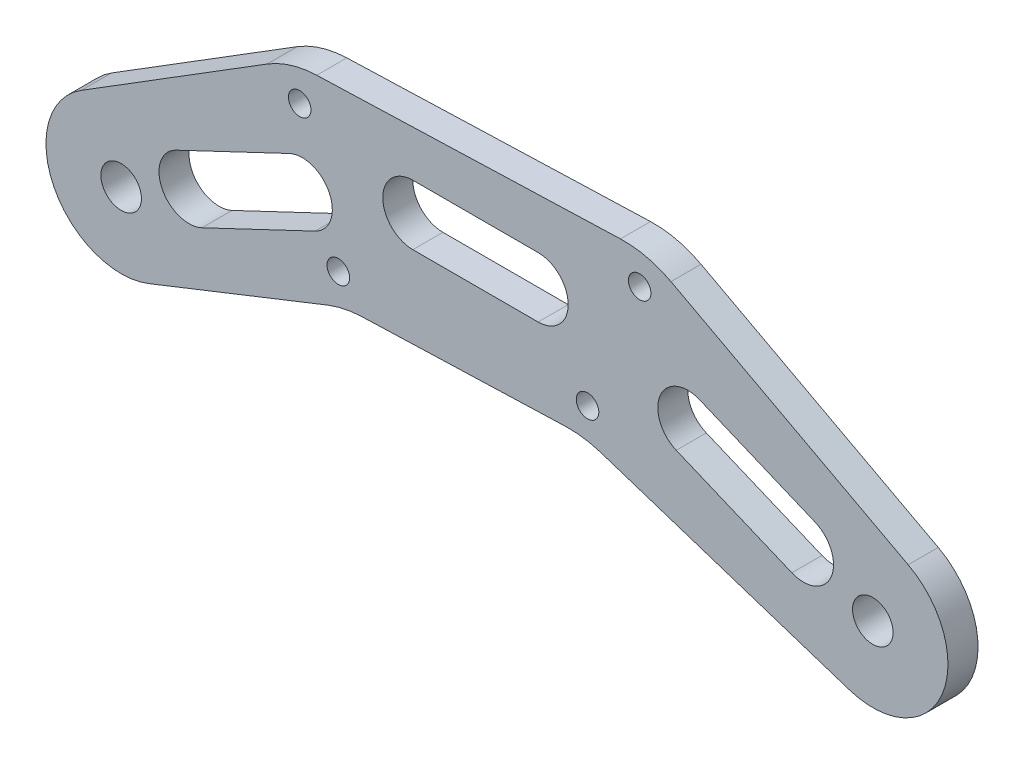
SolidWorks part; units mm, degrees
material "1060 Alloy"
ref_plane "Front Plane" through (0, 0, 0) normal (0, 0, 1) x (1, 0, 0)
ref_plane "Top Plane" through (0, 0, 0) normal (0, 1, 0) x (1, 0, 0)
ref_plane "Right Plane" through (0, 0, 0) normal (1, 0, 0) x (0, 0, -1)
sketch "Sketch1" plane through (0, 0, 0) normal (0, 0, 1) x (1, 0, 0)
  line L0 (-70.7116, -24.2666) -> (-32.512, -0.4802) construction
  line L1 (-32.512, -0.4802) -> (30.767, 1.6301) construction
  line L2 (30.767, 1.6301) -> (79.2884, -24.2671) construction
  line L3 (-65.1906, -38.2136) -> (-29.435, -24.0597)
  line L4 (-22.7403, -22.6668) -> (18.0348, -21.307)
  line L5 (-68.9461, -11.387) -> (-40.7958, 6.1419) construction
  line L6 (-78.6403, -11.5334) -> (-41.5781, 11.5449)
  line L7 (-31.6729, 14.5562) -> (28.928, 16.5771)
  line L8 (39.0118, 14.2324) -> (86.3513, -11.034)
  line L9 (74.6308, -38.5257) -> (24.9116, -22.2845)
  line L10 (-24.6554, -17.7279) -> (19.5563, -16.2535) construction
  line L11 (38.3913, 8.896) -> (76.6688, -11.5338) construction
  line L12 (68.2873, -31.1935) -> (44.8744, -23.5455) construction
  line L13 (-59.3074, -30.5072) -> (-37.2698, -21.7836) construction
  line L14 (-35.5233, 9.425) -> (-27.2422, -17.8142) construction
  line L15 (33.1117, 11.7138) -> (22.2738, -16.1629) construction
  line L16 (-1.2069, 10.6036) -> (-0.3226, -15.9159) construction
  line L17 (-29.3156, 9.632) -> (26.678, 11.4993) construction
  line L18 (-35.8839, 2.0162) -> (-31.4035, -12.7213) construction
  line L19 (-31.1001, 3.4706) -> (-24.6554, -17.7279) construction
  line L20 (32.905, 4.2829) -> (24.6539, -16.9403) construction
  line L21 (55.2105, -4.18) -> (49.1505, -15.5341) construction
  line L22 (33.6271, -19.8715) -> (24.6539, -16.9403) construction
  line L23 (28.2448, 6.0946) -> (19.5563, -16.2535) construction
  line L24 (-45.4998, -8.5675) -> (-42.0019, -14.185) construction
  line L26 (-85.7116, 18.7334) -> (94.2884, 18.7334) construction
  line L27 (-85.7116, 18.7334) -> (-85.7116, -39.2666) construction
  line L28 (-85.7116, -39.2666) -> (94.2884, -39.2666) construction
  line L29 (94.2884, 18.7334) -> (94.2884, -39.2666) construction
  arc A0 (-65.1906, -38.2136) -> (-78.6403, -11.5334) centre (-70.7116, -24.2666) cw
  arc A1 (74.6308, -38.5257) -> (86.3513, -11.034) centre (79.2884, -24.2671) ccw
  circle A2 centre (-70.7116, -24.2666) radius 4.05
  circle A3 centre (79.2884, -24.2671) radius 4.05
  arc A4 (-31.1001, 3.4706) -> (-29.3156, 9.632) centre (-35.0785, 7.9619) ccw construction
  arc A5 (-59.3074, -30.5072) -> (-68.9461, -11.387) centre (-70.7116, -24.2666) ccw construction
  arc A6 (76.6688, -11.5338) -> (68.2873, -31.1935) centre (79.2884, -24.2671) ccw construction
  arc A7 (26.678, 11.4993) -> (28.2448, 6.0946) centre (32.5513, 10.2724) ccw construction
  arc A8 (32.905, 4.2829) -> (38.3913, 8.896) centre (32.5513, 10.2724) ccw construction
  arc A9 (-40.7958, 6.1419) -> (-35.8839, 2.0162) centre (-35.0785, 7.9619) ccw construction
  arc A10 (24.9116, -22.2845) -> (18.0348, -21.307) centre (18.7014, -41.2959) ccw
  arc A11 (-29.435, -24.0597) -> (-22.7403, -22.6668) centre (-22.0738, -42.6557) cw
  arc A12 (28.928, 16.5771) -> (39.0118, 14.2324) centre (29.5946, -3.4118) cw
  arc A13 (-41.5781, 11.5449) -> (-31.6729, 14.5562) centre (-31.0063, -5.4327) cw
  arc A14 (44.8744, -23.5455) -> (33.6271, -19.8715) centre (39.5613, -20.7579) ccw construction
  arc A15 (-31.4035, -12.7213) -> (-37.2698, -21.7836) centre (-32.1371, -18.6763) ccw construction
  point P57 (-0.7648, -2.6561)
  dimension "D9" = 8.1
  dimension "D10" = 12
  dimension "D11" = 20
  dimension "D14" = 15
  dimension "D15" = 15
  dimension "D1" = 150
  dimension "D2" = 150
  dimension "D3" = 55
  dimension "D4" = 150
  dimension "D5" = 45
  dimension "D6" = 22.5
  dimension "D7" = 10
  dimension "D8" = 15
  dimension "D12" = 30.7
  dimension "D13" = 29.7
  dimension "D16" = 58
extrude "Boss-Extrude1" add sketch "Sketch1" along normal blind 6 contours L6 A13 L7 A12 L8 A1 L9 A10 L4 A11 L3 A0
sketch "Sketch2" plane through (0, 0, 6) normal (0, 0, 1) x (1, 0, 0)
  line L6 (-35.0785, 7.9619) -> (-27.3698, -17.2008) construction
  line L7 (32.7653, 10.2244) -> (22.3603, -15.5547) construction
  line L12 (-67.399, -32.6348) -> (-31.6434, -18.4809)
  line L13 (-22.9403, -16.6701) -> (17.8348, -15.3104)
  line L14 (26.7746, -16.5811) -> (76.4939, -32.8222)
  line L15 (83.5262, -16.3272) -> (36.1866, 8.9391)
  line L16 (29.128, 10.5804) -> (-31.4729, 8.5595)
  line L17 (-38.4065, 6.4516) -> (-75.4688, -16.6266)
  line L18 (-67.399, -32.6348) -> (-31.6434, -18.4809) construction
  line L19 (-22.9403, -16.6701) -> (17.8348, -15.3104) construction
  line L20 (26.7746, -16.5811) -> (76.4939, -32.8222) construction
  line L21 (83.5262, -16.3272) -> (36.1866, 8.9391) construction
  line L22 (29.128, 10.5804) -> (-31.4729, 8.5595) construction
  line L23 (-38.4065, 6.4516) -> (-75.4688, -16.6266) construction
  arc A12 (-75.4688, -16.6266) -> (-67.399, -32.6348) centre (-70.7116, -24.2666) ccw
  arc A13 (-22.9403, -16.6701) -> (-31.6434, -18.4809) centre (-22.0738, -42.6557) ccw
  arc A14 (26.7746, -16.5811) -> (17.8348, -15.3104) centre (18.7014, -41.2959) ccw
  arc A15 (76.4939, -32.8222) -> (83.5262, -16.3272) centre (79.2884, -24.2671) ccw
  arc A16 (36.1866, 8.9391) -> (29.128, 10.5804) centre (29.5946, -3.4118) ccw
  arc A17 (-31.4729, 8.5595) -> (-38.4065, 6.4516) centre (-31.0063, -5.4327) ccw
  arc A18 (-75.4688, -16.6266) -> (-67.399, -32.6348) centre (-70.7116, -24.2666) ccw construction
  arc A19 (-22.9403, -16.6701) -> (-31.6434, -18.4809) centre (-22.0738, -42.6557) ccw construction
  arc A20 (26.7746, -16.5811) -> (17.8348, -15.3104) centre (18.7014, -41.2959) ccw construction
  arc A21 (76.4939, -32.8222) -> (83.5262, -16.3272) centre (79.2884, -24.2671) ccw construction
  arc A22 (36.1866, 8.9391) -> (29.128, 10.5804) centre (29.5946, -3.4118) ccw construction
  arc A23 (-31.4729, 8.5595) -> (-38.4065, 6.4516) centre (-31.0063, -5.4327) ccw construction
  dimension "D1" = 6
hole_wizard "M4 Clearance Hole1" positions "3DSketch1" profile "Sketch3" hole size "M4" standard "DIN"
sketch3d "3DSketch1"
  point P0 (-35.0785, 7.9619, 6)
  point P3 (-27.3698, -17.2008, 6)
  point P6 (32.7653, 10.2244, 6)
  point P9 (22.3603, -15.5547, 6)
sketch "Sketch3" plane through (-35.0785, 7.9619, 6) normal (1, 0, 0) x (0, -1, 0)
  line L0 (0, 0) -> (0, 82.3119)
  line L1 (0, 82.3119) -> (2.25, 80.96)
  line L2 (2.25, 80.96) -> (2.25, 0)
  line L5 (2.25, 0) -> (0, 0)
  line L10 (0, 82.3119) -> (-2.25, 80.96) construction
  line L11 (0, -6.35) -> (0, 107.95) construction
  dimension "Hole Dia." = 4.5
  dimension "Hole Depth" = 80.96
  dimension "Drill Angle" = 118
sketch "Sketch4" plane through (0, 0, 6) normal (0, 0, 1) x (1, 0, 0)
  line L0 (-57.1589, -17.838) -> (-34.5712, -7.1237) construction
  line L1 (-59.7304, -12.4169) -> (-37.1427, -1.7027)
  line L2 (-54.5875, -23.259) -> (-31.9998, -12.5448)
  line L3 (-70.7116, -24.2666) -> (-31.0063, -5.4327) construction
  line L4 (65.447, -18.4866) -> (42.378, -8.8523) construction
  line L5 (63.1348, -24.0231) -> (40.0657, -14.3889)
  line L6 (67.7592, -12.95) -> (44.6902, -3.3157)
  line L7 (79.2884, -24.2671) -> (27.5628, -2.6651) construction
  line L8 (-12.5, 0) -> (12.5, 0) construction
  line L9 (-12.5, 6) -> (12.5, 6)
  line L10 (-12.5, -6) -> (12.5, -6)
  line L12 (32.7653, 10.2244) -> (22.3603, -15.5547) construction
  arc A0 (-59.7304, -12.4169) -> (-54.5875, -23.259) centre (-57.1589, -17.838) ccw
  arc A1 (-31.9998, -12.5448) -> (-37.1427, -1.7027) centre (-34.5712, -7.1237) ccw
  arc A2 (63.1348, -24.0231) -> (67.7592, -12.95) centre (65.447, -18.4866) ccw
  arc A3 (44.6902, -3.3157) -> (40.0657, -14.3889) centre (42.378, -8.8523) ccw
  circle A4 centre (79.2884, -24.2671) radius 4.05 construction
  arc A5 (-12.5, 6) -> (-12.5, -6) centre (-12.5, 0) ccw
  arc A6 (12.5, -6) -> (12.5, 6) centre (12.5, 0) ccw
  point P2 (-45.8651, -12.4809)
  point P13 (53.9125, -13.6694)
  point P25 (0, 0)
  dimension "D4" = 6
  dimension "D1" = 15
  dimension "D2" = 25
  dimension "D3" = 15
extrude "Cut-Extrude1" cut sketch "Sketch4" against normal through all
sketch "Sketch5" [suppressed] plane through (0, 0, 6) normal (0, 0, 1) x (1, 0, 0)
  line L0 (-85.7116, 18.7334) -> (-85.7116, -39.2666) construction
  line L1 (-85.7116, -39.2666) -> (94.2884, -39.2666) construction
  line L2 (-85.7116, 18.7334) -> (94.2884, 18.7334) construction
  line L3 (94.2884, 18.7334) -> (94.2884, -39.2666) construction
  arc A0 (-78.6403, -11.5334) -> (-65.1906, -38.2136) centre (-70.7116, -24.2666) ccw construction
  arc A1 (74.6308, -38.5257) -> (86.3513, -11.034) centre (79.2884, -24.2671) ccw construction
  dimension "D1" = 58
equation "\"¸12\"=10.9401"
